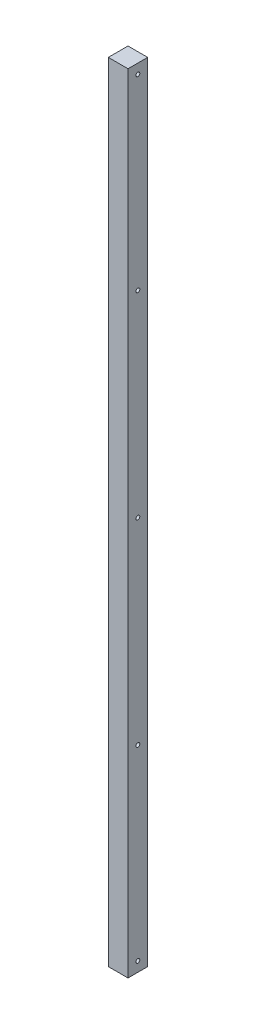
SolidWorks part; units mm, degrees
ref_plane "Спереди" through (0, 0, 0) normal (0, 0, 1) x (1, 0, 0)
ref_plane "Сверху" through (0, 0, 0) normal (0, 1, 0) x (1, 0, 0)
ref_plane "Справа" through (0, 0, 0) normal (1, 0, 0) x (0, 0, -1)
other "Configuration Table"
sketch "Эскиз1" plane through (0, 0, 0) normal (0, 1, 0) x (1, 0, 0)
  line L1 (25, 25) -> (-25, 25)
  line L2 (25, 25) -> (25, -25)
  line L3 (25, -25) -> (-25, -25)
  line L4 (-25, 25) -> (-25, -25)
  line L5 (25, 25) -> (-25, -25) construction
  line L6 (25, -25) -> (-25, 25) construction
  point P0 (0, 0)
extrude "Бобышка-Вытянуть2" add sketch "Эскиз1" along normal blind 2000 contours L4 L3 L2 L1
sketch "Эскиз2" plane through (25, 0, 0) normal (1, 0, 0) x (0, 0, -1)
  line L0 (-25, 2000) -> (25, 2000) construction
  line L1 (-25, 2000) -> (-25, 1950) construction
  line L2 (-25, 2000) -> (-25, 0) construction
  line L3 (-25, 1950) -> (25, 1950) construction
  line L4 (25, 2000) -> (25, 0) construction
  line L5 (25, 1950) -> (25, 2000) construction
  line L6 (25, 2000) -> (-25, 1950) construction
  line L7 (-25, 0) -> (25, 0) construction
  line L8 (25, 0) -> (25, 50) construction
  line L9 (25, 50) -> (-25, 50) construction
  line L10 (-25, 50) -> (-25, 0) construction
  line L11 (-25, 0) -> (25, 50) construction
  circle A0 centre (0, 1975) radius 5
  circle A1 centre (0, 25) radius 5
extrude "Вырез-Вытянуть1" cut sketch "Эскиз2" against normal through all
sketch "Эскиз3" plane through (25, 0, 0) normal (1, 0, 0) x (0, 0, -1)
  line L0 (0, 2000) -> (0, 0) construction
  line L1 (25, 2000) -> (-25, 2000) construction
  circle A0 centre (0, 1000) radius 5
extrude "Вырез-Вытянуть2" cut sketch "Эскиз3" against normal through all
sketch "Эскиз4" plane through (25, 0, 0) normal (1, 0, 0) x (0, 0, -1)
  line L0 (0, 2000) -> (0, 0) construction
  line L1 (25, 2000) -> (-25, 2000) construction
  line L2 (0, 0) -> (0, 1000) construction
  line L3 (0, 1000) -> (0, 0) construction
  line L4 (0, 0) -> (0, 1000) construction
  line L5 (0, 1000) -> (0, 2000) construction
  line L6 (0, 1000) -> (0, 0) construction
  circle A0 centre (0, 1500) radius 5
  circle A1 centre (0, 500) radius 5
extrude "Вырез-Вытянуть3" cut sketch "Эскиз4" against normal through all
